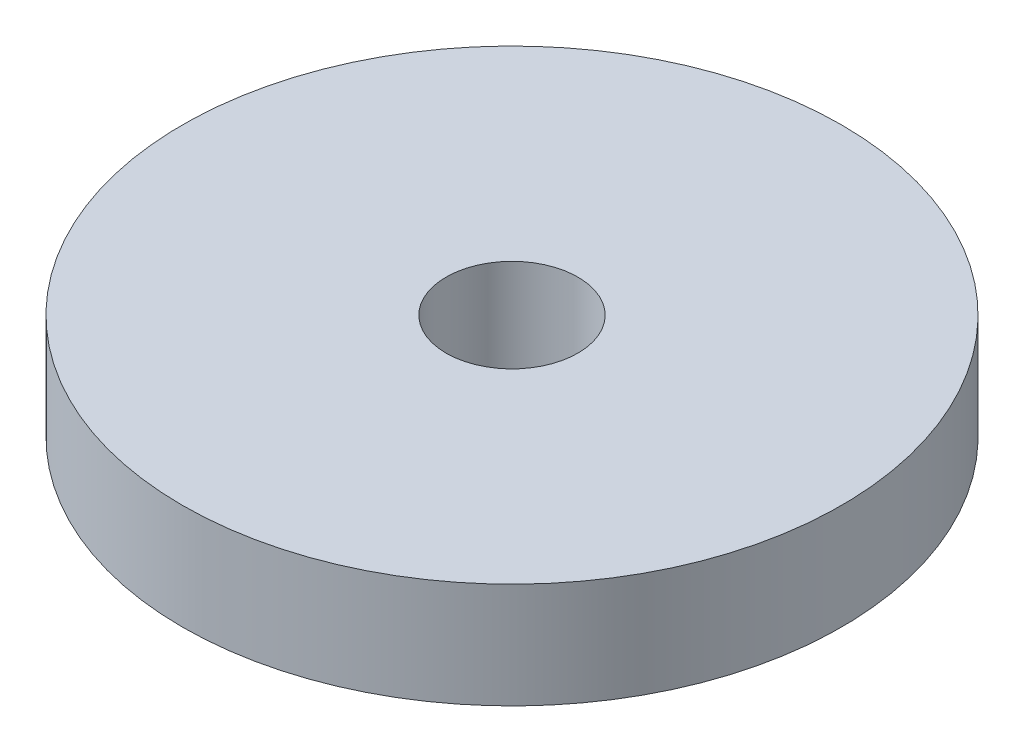
SolidWorks part; units mm, degrees
material "S-Glass Fiber"
ref_plane "Front Plane" through (0, 0, 0) normal (0, 0, 1) x (1, 0, 0)
ref_plane "Top Plane" through (0, 0, 0) normal (0, 1, 0) x (1, 0, 0)
ref_plane "Right Plane" through (0, 0, 0) normal (1, 0, 0) x (0, 0, -1)
sketch "Sketch1" plane through (0, 0, 0) normal (0, 1, 0) x (1, 0, 0)
  circle A0 centre (0, 0) radius 15.875
  circle A1 centre (0, 0) radius 3.175
  dimension "D1" = 6.35
  dimension "D2" = 31.75
extrude "Boss-Extrude1" add sketch "Sketch1" along normal blind 5.08
